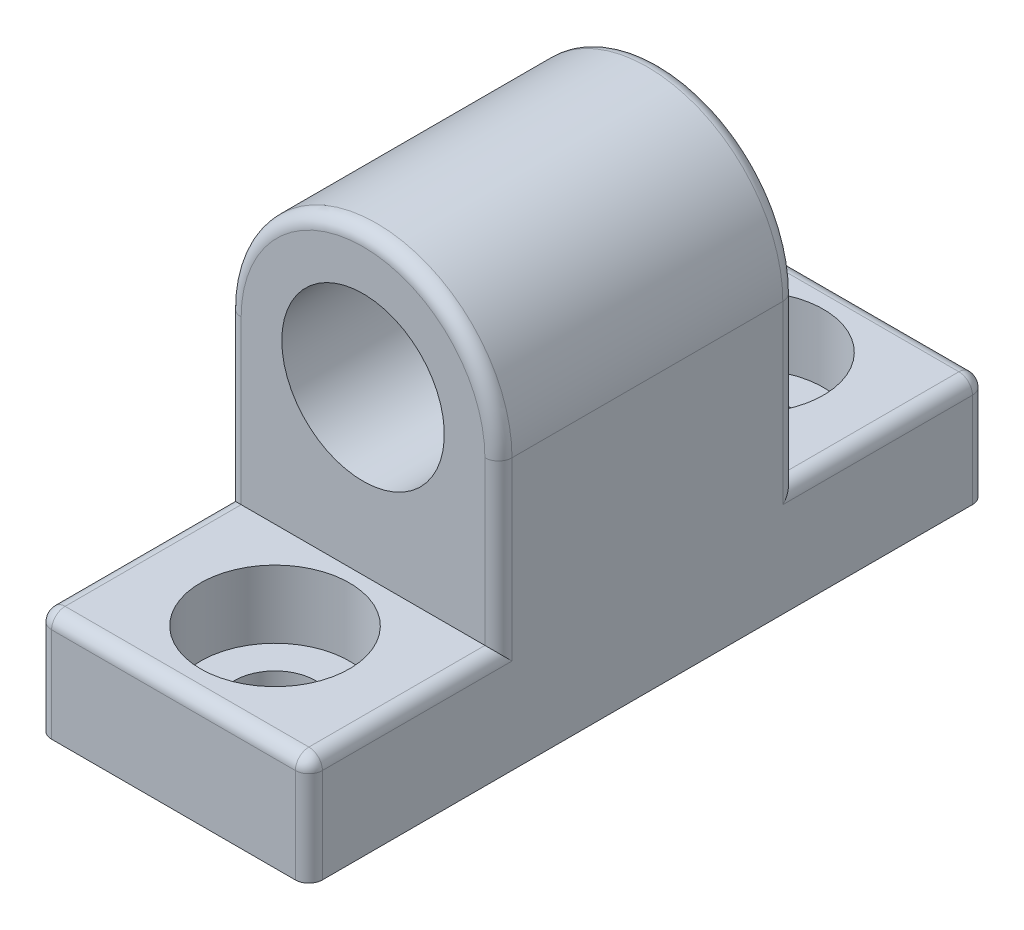
SolidWorks part; units mm, degrees
ref_plane "Спереди" through (0, 0, 0) normal (0, 0, 1) x (1, 0, 0)
ref_plane "Сверху" through (0, 0, 0) normal (0, 1, 0) x (1, 0, 0)
ref_plane "Справа" through (0, 0, 0) normal (1, 0, 0) x (0, 0, -1)
sketch "Эскиз1" plane through (0, 0, 0) normal (0, 0, 1) x (1, 0, 0)
  line L1 (-10, 0) -> (10, 0)
  line L2 (-10, 0) -> (-10, 20)
  line L4 (10, 0) -> (10, 20)
  arc A0 (10, 20) -> (-10, 20) centre (0, 20) ccw
  circle A1 centre (0, 20) radius 6
  dimension "D2" = 30
  dimension "D3" = 12
  dimension "D1" = 20
extrude "Бобышка-Вытянуть1" add sketch "Эскиз1" along normal mid plane 50
sketch "Эскиз2" plane through (0, 0, 0) normal (1, 0, 0) x (0, 0, -1)
  line L0 (-25, 0) -> (25, 0) construction
  line L1 (32.9029, 8) -> (11, 8)
  line L2 (32.9029, 8) -> (32.9029, 39.1917)
  line L3 (32.9029, 39.1917) -> (11, 39.1917)
  line L4 (11, 8) -> (11, 39.1917)
  line L5 (-34.5139, 8) -> (-11, 8)
  line L6 (-34.5139, 8) -> (-34.5139, 41.7756)
  line L7 (-34.5139, 41.7756) -> (-11, 41.7756)
  line L8 (-11, 8) -> (-11, 41.7756)
  line L9 (0, -6.0405) -> (0, 41.7756) construction
  line L10 (25, 20) -> (25, 0) construction
  dimension "D1" = 8
  dimension "D2" = 14
extrude "Вырез-Вытянуть1" cut sketch "Эскиз2" against normal through all and the other way through all
sketch "Эскиз3" plane through (-10, 0, 0) normal (-1, 0, 0) x (0, 0, 1)
  circle A0 centre (0, 20) radius 2.5
  dimension "D1" = 5
  dimension "D2" = 20
extrude "Вырез-Вытянуть2" cut sketch "Эскиз3" against normal up to next
sketch "Эскиз4" plane through (0, 0, 0) normal (0, -1, 0) x (-1, 0, 0)
  circle A0 centre (0, 0) radius 3
  dimension "D1" = 6
extrude "Вырез-Вытянуть3" cut sketch "Эскиз4" against normal blind 12
sketch "Эскиз5" plane through (0, 8, 0) normal (0, 1, 0) x (1, 0, 0)
  line L0 (0, 17.5) -> (0, -17.5) construction
  circle A0 centre (0, 17.5) radius 5.5
  circle A1 centre (0, -17.5) radius 5.5
  dimension "D1" = 11
  dimension "D2" = 35
extrude "Вырез-Вытянуть4" cut sketch "Эскиз5" against normal blind 5
sketch "Эскиз6" plane through (0, 3, 0) normal (0, 1, 0) x (1, 0, 0)
  circle A0 centre (0, 17.5) radius 3
  circle A1 centre (0, -17.5) radius 3
  circle A2 centre (0, 17.5) radius 5.5 construction
  dimension "D1" = 6
extrude "Вырез-Вытянуть5" cut sketch "Эскиз6" against normal through all
fillet "Скругление1" radius 1 16 edges at (10, 14, 11) (10, 14, -11) (10, 8, -18) (10, 4, 25) (-10, 4, 25) (-10, 8, 18) (0, 8, 25) (10, 8, 18) (0, 30, 11) (-10, 14, 11) (-10, 14, -11) (0, 30, -11) (-10, 4, -25) (0, 8, -25) (-10, 8, -18) (10, 4, -25)
